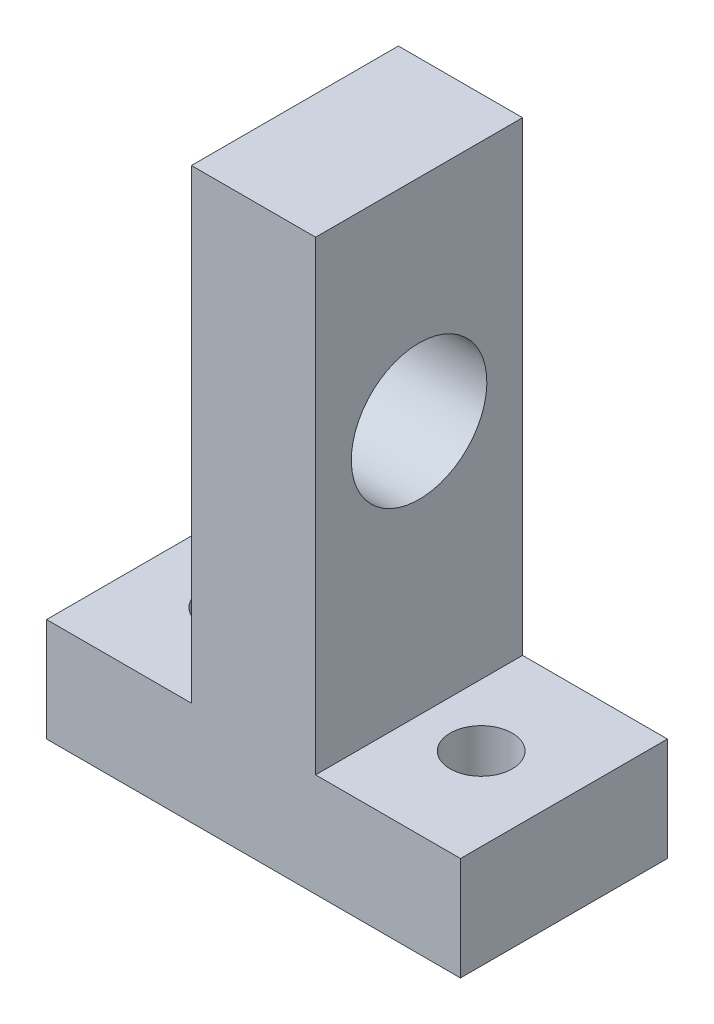
SolidWorks part; units mm, degrees
ref_plane "Alzado" through (0, 0, 0) normal (0, 0, 1) x (1, 0, 0)
ref_plane "Planta" through (0, 0, 0) normal (0, 1, 0) x (1, 0, 0)
ref_plane "Vista lateral" through (0, 0, 0) normal (1, 0, 0) x (0, 0, -1)
sketch "Croquis1" plane through (0, 0, 0) normal (0, 0, 1) x (1, 0, 0)
  line L0 (3, 13.75) -> (-3, 13.75)
  line L1 (-3, 13.75) -> (-3, -8.75)
  line L2 (-3, -8.75) -> (-10, -8.75)
  line L3 (-10, -8.75) -> (-10, -13.75)
  line L4 (-10, -13.75) -> (10, -13.75)
  line L5 (0, -13.75) -> (0, 13.75)
  line L6 (0, 28.2693) -> (0, -29.9167) construction
  line L7 (10, -8.75) -> (10, -13.75)
  line L8 (3, -8.75) -> (10, -8.75)
  line L9 (3, 13.75) -> (3, -8.75)
  point P10 (0, 0)
  dimension "D1" = 27.5
  dimension "D2" = 3
  dimension "D3" = 10
  dimension "D4" = 5
extrude "Saliente-Extruir1" add sketch "Croquis1" along normal mid plane 10 contours L9 L0 L5 L4 L7 L8 | L4 L5 L0 L1 L2 L3
sketch "Croquis4" plane through (3, 0, 0) normal (1, 0, 0) x (0, 0, -1)
  line L0 (0, 12.8173) -> (0, -5.1206) construction
  line L1 (-5, -13.75) -> (5, -13.75) construction
  circle A0 centre (0, 3.55) radius 3.275
  dimension "D2" = 6.55
  dimension "D1" = 17.3
extrude "Cortar-Extruir3" cut sketch "Croquis4" against normal blind 15
sketch "Croquis5" plane through (0, -13.75, 0) normal (0, -1, 0) x (1, 0, 0)
  line L0 (12.601, 0) -> (-13.2445, 0) construction
  line L1 (0, 4.0216) -> (0, -6.2022) construction
  circle A0 centre (-6, 0) radius 1.5
  circle A1 centre (6, 0) radius 1.5
  dimension "D1" = 3
  dimension "D2" = 6
extrude "Cortar-Extruir4" cut sketch "Croquis5" against normal blind 10
